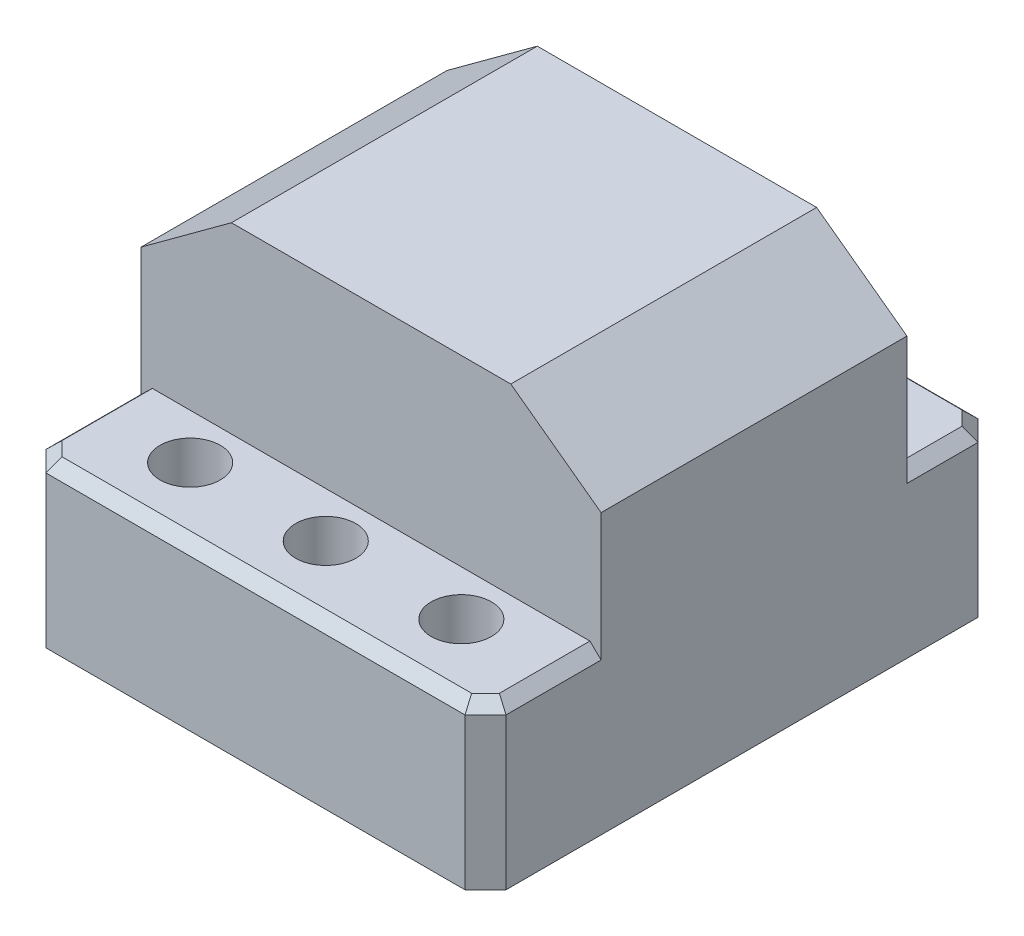
SolidWorks part; units mm, degrees
ref_plane "Front Plane" through (0, 0, 0) normal (0, 0, 1) x (1, 0, 0)
ref_plane "Top Plane" through (0, 0, 0) normal (0, 1, 0) x (1, 0, 0)
ref_plane "Right Plane" through (0, 0, 0) normal (1, 0, 0) x (0, 0, -1)
sketch "Sketch1" plane through (0, 0, 0) normal (0, 1, 0) x (1, 0, 0)
  line L1 (0, 0) -> (48.514, 0)
  line L2 (0, 0) -> (0, -54.102)
  line L3 (0, -54.102) -> (48.514, -54.102)
  line L4 (48.514, 0) -> (48.514, -54.102)
  dimension "D1" = 48.514
  dimension "D2" = 54.102
extrude "Boss-Extrude1" add sketch "Sketch1" along normal blind 17.1196
sketch "Sketch3" plane through (0, 17.1196, 0) normal (0, 1, 0) x (1, 0, 0)
  line L0 (0, 0) -> (0, -54.102) construction
  line L1 (0, -9.652) -> (48.514, -9.652)
  line L2 (0, -9.652) -> (0, -41.91)
  line L3 (0, -41.91) -> (48.514, -41.91)
  line L4 (48.514, -9.652) -> (48.514, -41.91)
  line L5 (48.514, -54.102) -> (48.514, 0) construction
  line L6 (48.514, 0) -> (0, 0) construction
  dimension "D1" = 9.652
  dimension "D2" = 32.258
extrude "Boss-Extrude3" add sketch "Sketch3" along normal blind 19.304
chamfer "Chamfer1" distance 6.985 distance2 9.525 2 edges at (48.514, 36.4236, 25.781) (0, 36.4236, 25.781)
chamfer "Chamfer3" distance 2.159 4 edges at (0, 8.5598, 0) (48.514, 8.5598, 0) (48.514, 8.5598, 54.102) (0, 8.5598, 54.102)
chamfer "Chamfer4" distance 1.143 angle 46 10 edges at (48.514, 17.1196, 5.9055) (47.4345, 17.1196, 1.0795) (24.257, 17.1196, 0) (1.0795, 17.1196, 1.0795) (0, 17.1196, 5.9055) (0, 17.1196, 46.9265) (1.0795, 17.1196, 53.0225) (24.257, 17.1196, 54.102) (47.4345, 17.1196, 53.0225) (48.514, 17.1196, 46.9265)
sketch "Sketch4" plane through (0, 17.1196, 0) normal (0, 1, 0) x (1, 0, 0)
  line L0 (24.257, -52.9184) -> (24.257, -41.91) construction
  line L1 (2.6493, -52.9184) -> (45.8647, -52.9184) construction
  line L2 (1.1836, -41.91) -> (47.3304, -41.91) construction
  circle A0 centre (24.257, -46.6954) radius 3.175
  point P6 (24.257, -49.8704)
  dimension "D1" = 6.35
  dimension "D2" = 3.048
extrude "Cut-Extrude1" cut sketch "Sketch4" against normal blind 5.08
pattern_linear "LPattern1" count 2 spacing 14.3002 along (1, 0, 0) count 2 spacing 14.3002 along (-1, 0, 0) of "Cut-Extrude1"
